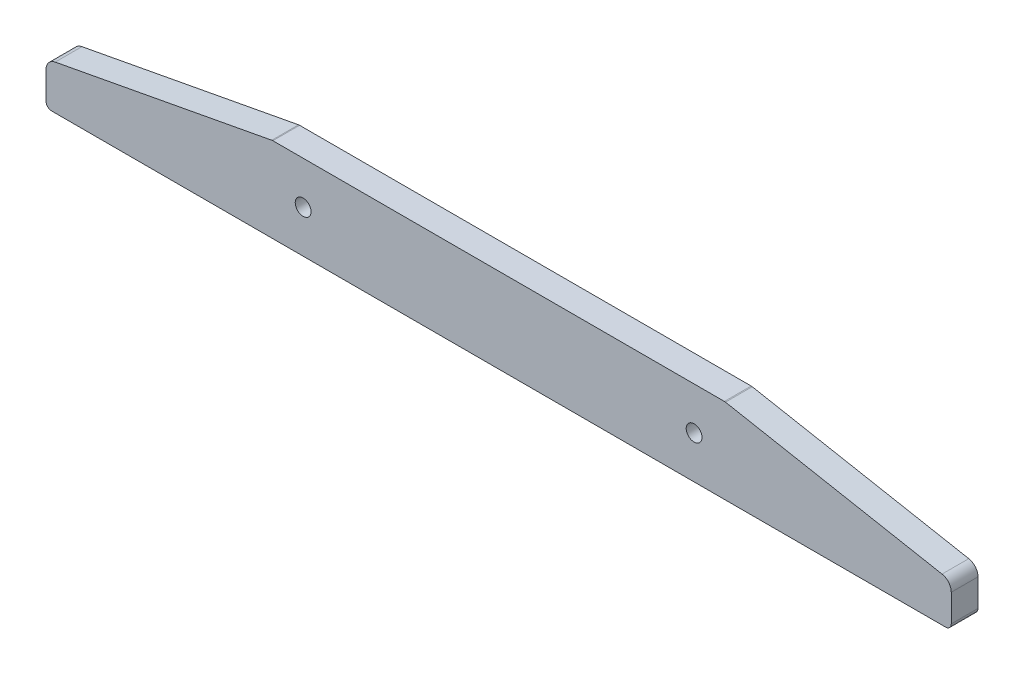
SolidWorks part; units mm, degrees
ref_plane "Front Plane" through (0, 0, 0) normal (0, 0, 1) x (1, 0, 0)
ref_plane "Top Plane" through (0, 0, 0) normal (0, 1, 0) x (1, 0, 0)
ref_plane "Right Plane" through (0, 0, 0) normal (1, 0, 0) x (0, 0, -1)
sketch "Sketch1" plane through (0, 0, 0) normal (0, 0, 1) x (1, 0, 0)
  line L0 (0, 0) -> (0, 19.05)
  line L1 (0, 19.05) -> (50.8, 19.05)
  line L2 (50.8, 19.05) -> (101.6, 9.525)
  line L3 (101.6, 9.525) -> (101.6, 0)
  line L4 (101.6, 0) -> (0, 0)
  dimension "D1" = 50.8
  dimension "D2" = 101.6
  dimension "D3" = 19.05
  dimension "D4" = 9.525
extrude "Boss-Extrude1" add sketch "Sketch1" along normal blind 6
mirror "Mirror1" about plane through (0, 0, 6) normal (1, 0, 0) of "Boss-Extrude1"
fillet "Fillet1" radius 2.54 2 edges at (101.6, 9.525, 3) (-101.6, 9.525, 3)
fillet "Fillet2" radius 1.27 4 edges at (-101.6, 0, 3) (-50.8, 19.05, 3) (50.8, 19.05, 3) (101.6, 0, 3)
sketch "Sketch2" plane through (0, 0, 6) normal (0, 0, 1) x (1, 0, 0)
  line L0 (0, 0) -> (0, 19.05) construction
  line L1 (-100.33, 0) -> (100.33, 0) construction
  line L2 (50.682, 19.05) -> (-50.682, 19.05) construction
  line L3 (0, 9.525) -> (-43.8785, 9.525) construction
  line L4 (0, 9.525) -> (43.8785, 9.525) construction
  circle A0 centre (-43.8785, 9.525) radius 1.778
  circle A1 centre (43.8785, 9.525) radius 1.778
  dimension "D1" = 3.556
  dimension "D2" = 87.757
extrude "Cut-Extrude1" cut sketch "Sketch2" against normal through all
